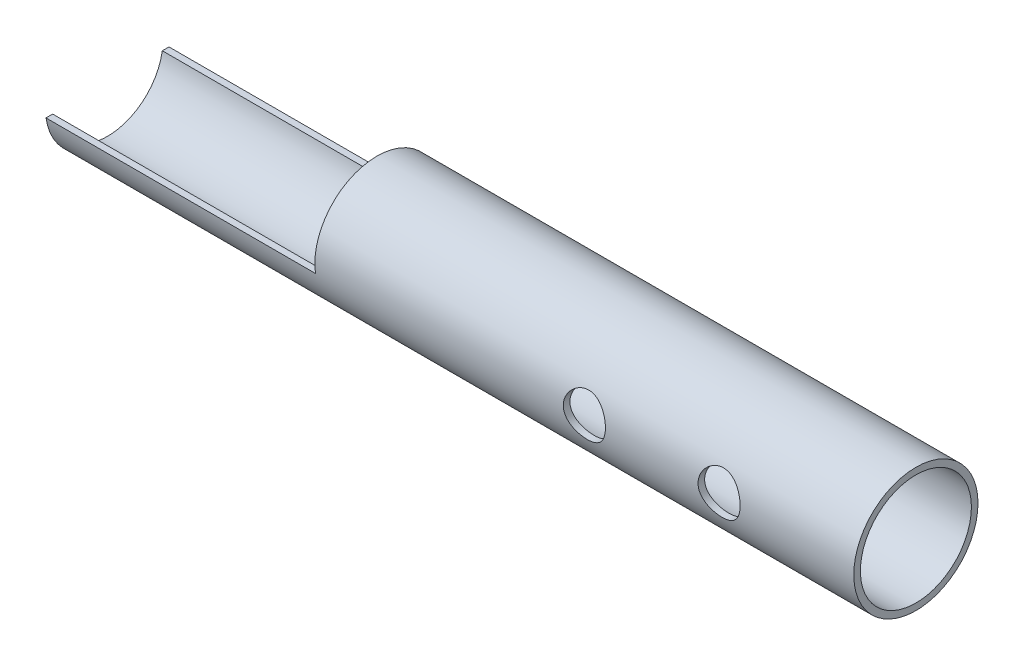
SolidWorks part; units mm, degrees
material "Galvanized Steel"
ref_plane "Front Plane" through (0, 0, 0) normal (0, 0, 1) x (1, 0, 0)
ref_plane "Top Plane" through (0, 0, 0) normal (0, 1, 0) x (1, 0, 0)
ref_plane "Right Plane" through (0, 0, 0) normal (1, 0, 0) x (0, 0, -1)
sketch "Sketch3" plane through (0, 0, 0) normal (1, 0, 0) x (0, 0, -1)
  circle A0 centre (0, 0) radius 10.4648
  circle A1 centre (0, 0) radius 11.7094
  dimension "D1" = 20.9296
  dimension "D2" = 23.4188
extrude "Boss-Extrude1" add sketch "Sketch3" along normal blind 152.4
sketch "Sketch4" plane through (0, 0, 0) normal (0, 0, 1) x (1, 0, 0)
  line L0 (0, 17.3929) -> (50.8, 17.3929)
  line L1 (50.8, 17.3929) -> (50.8, -1.6571)
  line L2 (50.8, -1.6571) -> (0, -1.6571)
  line L3 (0, -1.6571) -> (0, 17.3929)
  dimension "D1" = 19.05
extrude "Cut-Extrude1" cut sketch "Sketch4" against normal through all and the other way through all
sketch "Sketch5" plane through (152.4, 0, 0) normal (1, 0, 0) x (0, 0, -1)
  point P0 (0, 0)
ref_plane "Plane1" through (0, 0, 11.7094) normal (0, 0, 1) x (1, 0, 0)
sketch "Sketch8" plane through (0, 0, 11.7094) normal (0, 0, 1) x (1, 0, 0)
  circle A0 centre (101.6, 0.381) radius 3.9688 construction
  circle A1 centre (127, 0.381) radius 3.9688 construction
  circle A2 centre (101.6, 0.381) radius 3.9688
  circle A3 centre (127, 0.381) radius 3.9688
extrude "Cut-Extrude2" cut sketch "Sketch8" against normal through all
